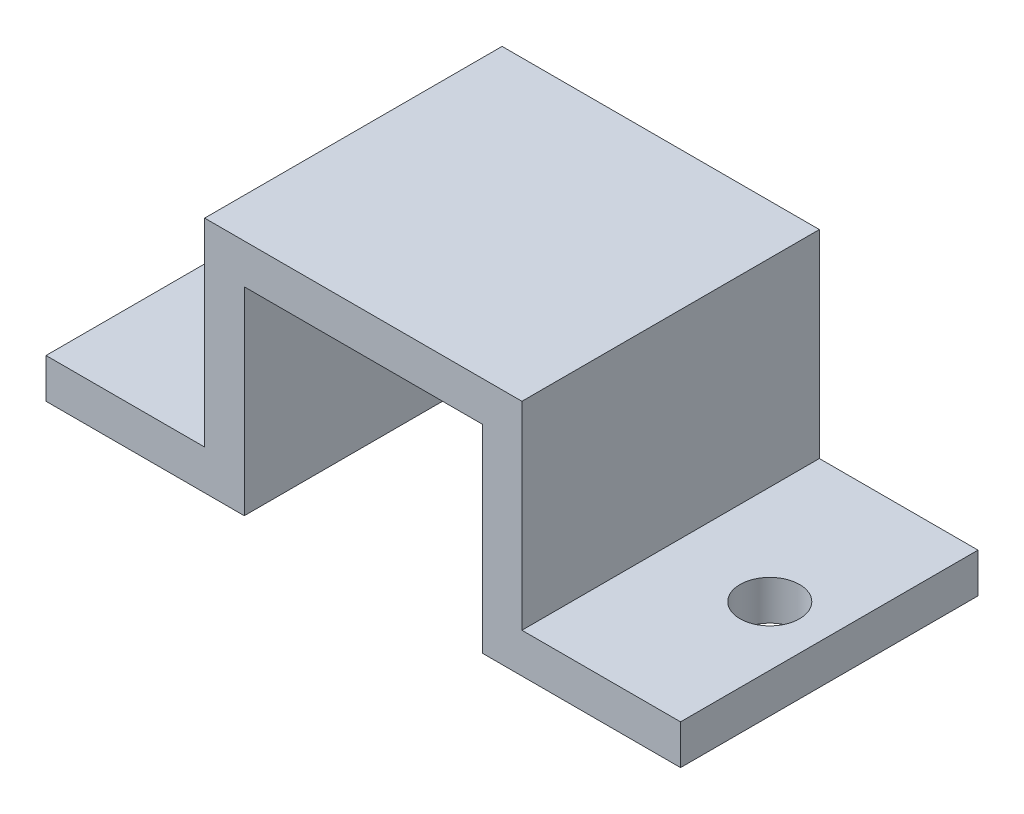
SolidWorks part; units mm, degrees
ref_plane "Front Plane" through (0, 0, 0) normal (0, 0, 1) x (1, 0, 0)
ref_plane "Top Plane" through (0, 0, 0) normal (0, 1, 0) x (1, 0, 0)
ref_plane "Right Plane" through (0, 0, 0) normal (1, 0, 0) x (0, 0, -1)
sketch "Sketch1" plane through (0, 0, 0) normal (0, 0, 1) x (1, 0, 0)
  line L1 (16, -6) -> (-16, -6)
  line L2 (16, -6) -> (16, 6)
  line L3 (16, 6) -> (-16, 6)
  line L4 (-16, -6) -> (-16, 6)
  line L5 (16, -6) -> (-16, 6) construction
  line L6 (16, 6) -> (-16, -6) construction
  line L7 (-6, -6) -> (6, -6)
  line L8 (-6, -6) -> (-6, 4)
  line L9 (-6, 4) -> (6, 4)
  line L10 (6, -6) -> (6, 4)
  line L11 (-8, 6) -> (-16, 6)
  line L12 (-8, 6) -> (-8, -4)
  line L13 (-8, -4) -> (-16, -4)
  line L14 (-16, 6) -> (-16, -4)
  line L15 (8, 6) -> (16, 6)
  line L16 (8, 6) -> (8, -4)
  line L17 (8, -4) -> (16, -4)
  line L18 (16, 6) -> (16, -4)
  point P0 (0, 0)
  point P16 (0, 4)
  dimension "D1" = 2
  dimension "D2" = 2
  dimension "D3" = 12
  dimension "D4" = 2
  dimension "D5" = 10
  dimension "D6" = 8
extrude "Boss-Extrude1" add sketch "Sketch1" along normal blind 15 contours L17 L16 L3 L12 L13 L4 L1 L8 L9 L10 L2
sketch "Sketch2" plane through (0, -4, 0) normal (0, 1, 0) x (1, 0, 0)
  line L0 (-13, -7.5) -> (13, -7.5) construction
  line L1 (8, 0) -> (16, 0) construction
  line L2 (-16, -15) -> (-16, 0) construction
  circle A0 centre (-13, -7.5) radius 1.5
  circle A1 centre (13, -7.5) radius 1.5
  point P4 (-16, -7.5)
  point P5 (0, -7.5)
  dimension "D2" = 3
  dimension "D1" = 3
extrude "Cut-Extrude1" cut sketch "Sketch2" against normal through all
